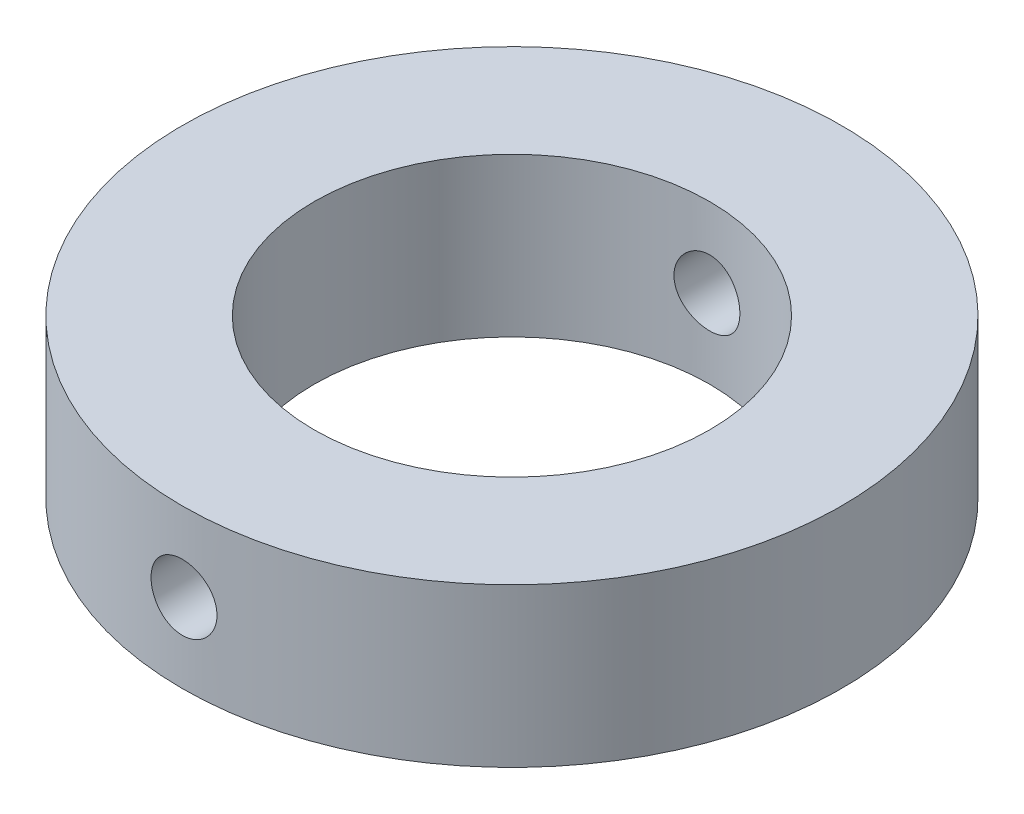
SolidWorks part; units mm, degrees
material "Plain Carbon Steel"
ref_plane "Front Plane" through (0, 0, 0) normal (0, 0, 1) x (1, 0, 0)
ref_plane "Top Plane" through (0, 0, 0) normal (0, 1, 0) x (1, 0, 0)
ref_plane "Right Plane" through (0, 0, 0) normal (1, 0, 0) x (0, 0, -1)
sketch "Sketch5" plane through (0, 0, 0) normal (0, 1, 0) x (1, 0, 0)
  circle A0 centre (0, 0) radius 25
  circle A1 centre (0, 0) radius 15
  dimension "D1" = 30
  dimension "D2" = 50
extrude "Boss-Extrude2" add sketch "Sketch5" along normal blind 12
sketch "Sketch6" plane through (0, 0, 0) normal (0, 0, 1) x (1, 0, 0)
  line L0 (0, 6) -> (25, 6) construction
  circle A0 centre (0, 6) radius 2.5
  dimension "D1" = 5
  dimension "D2" = 6
extrude "Cut-Extrude1" cut sketch "Sketch6" against normal through all both and the other way through all
